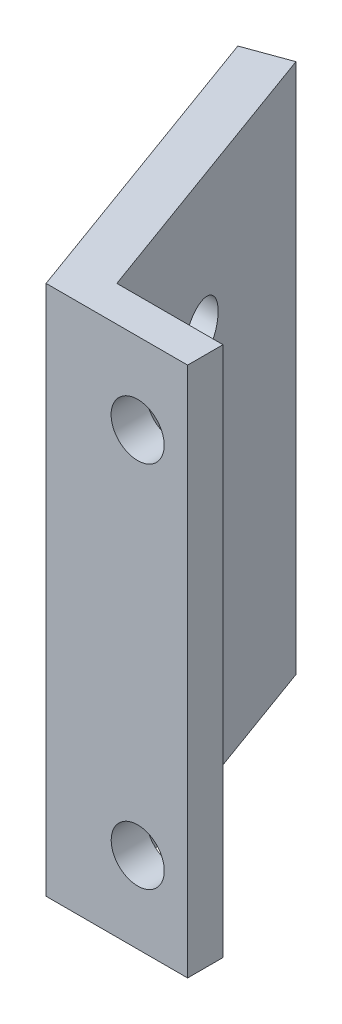
SolidWorks part; units mm, degrees
ref_plane "Front Plane" through (0, 0, 0) normal (0, 0, 1) x (1, 0, 0)
ref_plane "Top Plane" through (0, 0, 0) normal (0, 1, 0) x (1, 0, 0)
ref_plane "Right Plane" through (0, 0, 0) normal (1, 0, 0) x (0, 0, -1)
sketch "Sketch1" plane through (0, 0, 0) normal (0, 1, 0) x (1, 0, 0)
  line L3 (-4.5361, -6.2603) -> (3.4639, -6.2603)
  line L4 (3.4639, -4.2603) -> (3.4639, -6.2603)
  line L5 (-4.5361, -6.2603) -> (-10.7373, 10.7773)
  line L6 (-10.7373, 10.7773) -> (-8.3285, 11.6541)
  line L7 (-2.5361, -4.2603) -> (3.4639, -4.2603)
  line L8 (-2.5361, -4.2603) -> (-8.3285, 11.6541)
  point P0 (0.0704, -0.0352)
  dimension "D2" = 2
  dimension "D4" = 6
  dimension "D5" = 110
  dimension "D6" = 110
extrude "Boss-Extrude1" add sketch "Sketch1" along normal blind 30
sketch "Sketch2" plane through (0, 0, 4.2603) normal (0, 0, -1) x (-1, 0, 0)
  line L0 (2.5361, 30) -> (2.5361, 0) construction
  line L1 (2.5361, 30) -> (2.5361, 0) construction
  line L2 (-3.4639, 15) -> (9.7039, 15) construction
  line L3 (-3.4639, 30) -> (-3.4639, 0) construction
  circle A0 centre (-0.6389, 25.414) radius 1.5
  circle A1 centre (-0.6439, 4.59) radius 1.5
  dimension "D1" = 3.175
  dimension "D2" = 3
  dimension "D4" = 3
  dimension "D3" = 3.18
  dimension "D5" = 10.414
  dimension "D6" = 10.41
extrude "Cut-Extrude1" cut sketch "Sketch2" against normal blind 30
sketch "Sketch3" plane through (-2.5361, 0, 0) normal (1, 0, 0) x (0, 0, -1)
  line L0 (-4.2603, 30) -> (-4.2603, 0) construction
  line L3 (-4.2603, 30) -> (10.7397, 30) construction
  line L4 (-4.2603, 0) -> (10.7397, 0) construction
  circle A0 centre (3.2397, 22.5) radius 1.5
  circle A1 centre (3.2397, 7.5) radius 1.5
  dimension "D1" = 3
  dimension "D2" = 3
  dimension "D3" = 7.5
  dimension "D4" = 7.5
  dimension "D5" = 7.5
  dimension "D6" = 7.5
extrude "Cut-Extrude2" cut sketch "Sketch3" against normal blind 30
